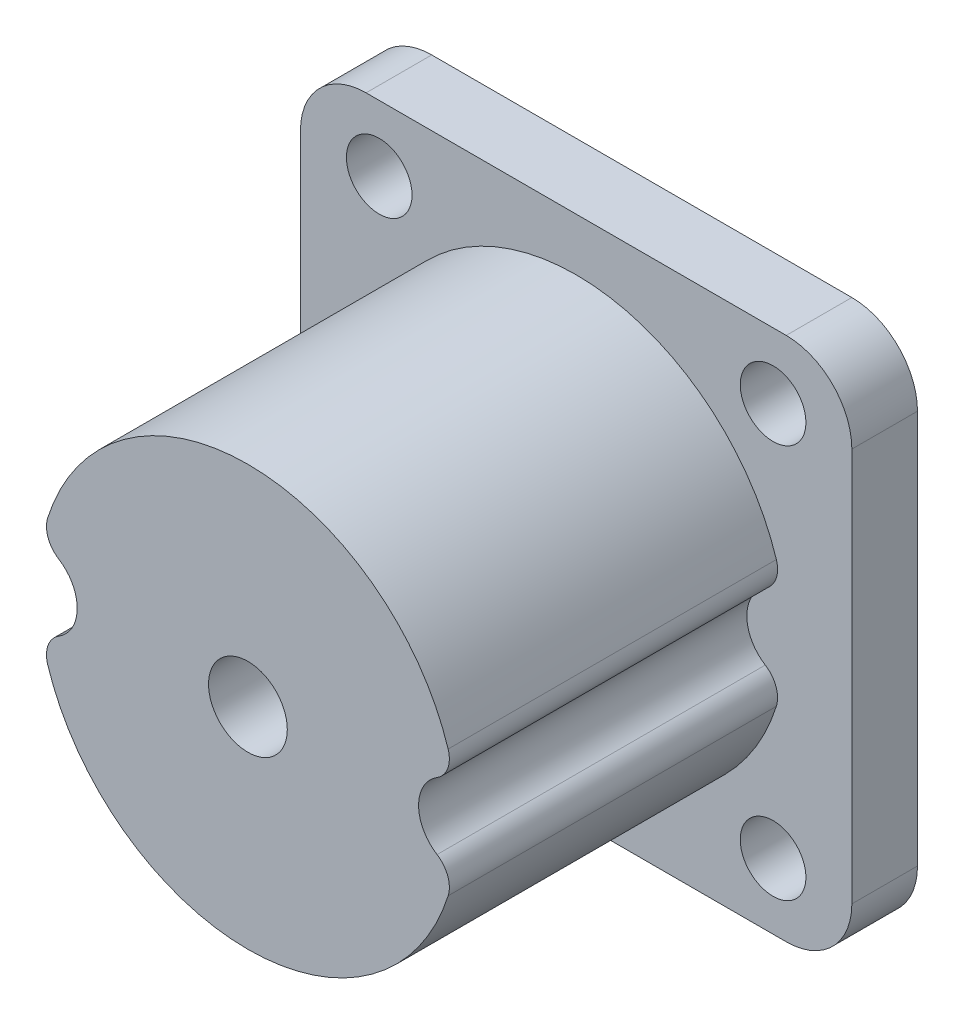
SolidWorks part; units mm, degrees
material "Alloy Steel"
ref_plane "Front Plane" through (0, 0, 0) normal (0, 0, 1) x (1, 0, 0)
ref_plane "Top Plane" through (0, 0, 0) normal (0, 1, 0) x (1, 0, 0)
ref_plane "Right Plane" through (0, 0, 0) normal (1, 0, 0) x (0, 0, -1)
sketch "Sketch1" plane through (0, 0, 0) normal (0, 0, 1) x (1, 0, 0)
  line L0 (0, 0) -> (12.8799, 0) construction
  line L1 (-21, -20) -> (21, -20)
  line L2 (-21, -20) -> (-21, 20)
  line L3 (-21, 20) -> (21, 20)
  line L4 (21, -20) -> (21, 20)
  line L5 (-21, -20) -> (21, 20) construction
  line L6 (-21, 20) -> (21, -20) construction
  circle A0 centre (0, 0) radius 3
  circle A1 centre (-15, 15) radius 2.5
  circle A2 centre (15, 15) radius 2.5
  circle A3 centre (15, -15) radius 2.5
  circle A4 centre (-15, -15) radius 2.5
  dimension "D1" = 6
  dimension "D4" = 5
  dimension "D7" = 15
  dimension "D9" = 5
  dimension "D2" = 42
  dimension "D3" = 40
  dimension "D5" = 15
  dimension "D6" = 15
  dimension "D8" = 15
extrude "Boss-Extrude1" add sketch "Sketch1" along normal blind 5
fillet "Fillet1" radius 5 4 edges at (21, -20, 2.5) (-21, -20, 2.5) (-21, 20, 2.5) (21, 20, 2.5)
sketch "Sketch2" plane through (0, 0, 5) normal (0, 0, 1) x (1, 0, 0)
  arc A0 (-15.7188, -2.9868) -> (15.7188, -2.9868) centre (0, 0) ccw
  arc A1 (-15.7188, -2.9868) -> (-15.7188, 2.9868) centre (-16, 0) ccw
  arc A2 (15.7188, 2.9868) -> (15.7188, -2.9868) centre (16, 0) ccw
  arc A3 (15.7188, 2.9868) -> (-15.7188, 2.9868) centre (0, 0) ccw
  circle A4 centre (0, 0) radius 3 construction
  circle A5 centre (0, 0) radius 3
  dimension "D1" = 32
  dimension "D2" = 6
  dimension "D3" = 6
extrude "Boss-Extrude2" add sketch "Sketch2" along normal blind 25
fillet "Fillet2" radius 2 4 edges at (-15.7188, -2.9868, 17.5) (-15.7188, 2.9868, 17.5) (15.7188, -2.9868, 17.5) (15.7188, 2.9868, 17.5)
